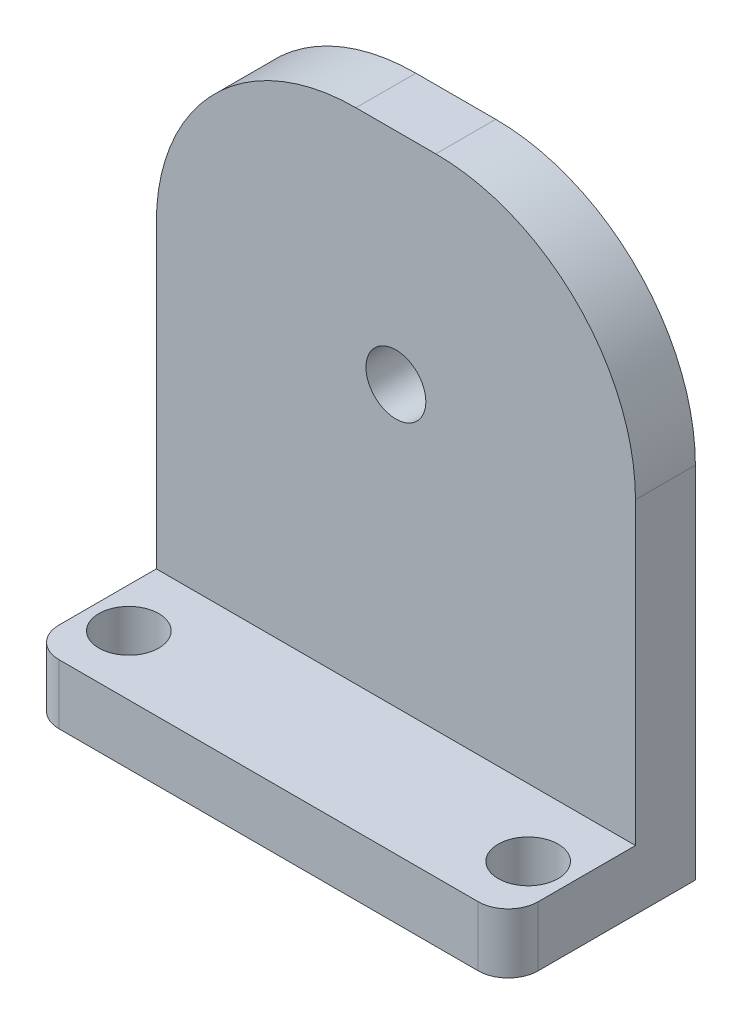
SolidWorks part; units mm, degrees
ref_plane "Front Plane" through (0, 0, 0) normal (0, 0, 1) x (1, 0, 0)
ref_plane "Top Plane" through (0, 0, 0) normal (0, 1, 0) x (1, 0, 0)
ref_plane "Right Plane" through (0, 0, 0) normal (1, 0, 0) x (0, 0, -1)
sketch "Sketch1" plane through (0, 0, 0) normal (0, 1, 0) x (1, 0, 0)
  line L0 (10, 0) -> (-10, 0) construction
  line L1 (12, 3) -> (-12, 3)
  line L2 (12, 3) -> (12, -1.5)
  line L3 (10.5, -3) -> (-10.5, -3)
  line L4 (-12, 3) -> (-12, -1.5)
  line L5 (12, 3) -> (-12, -3) construction
  line L6 (12, -3) -> (-12, 3) construction
  line L7 (-12, 3) -> (-12, 6.3757)
  line L8 (-12, 6.3757) -> (12, 6.3757)
  line L9 (12, 6.3757) -> (12, 3)
  line L10 (-12, 3) -> (11.5558, 3)
  circle A0 centre (-10, 0) radius 1.5
  circle A1 centre (10, 0) radius 1.5
  arc A2 (12, -1.5) -> (10.5, -3) centre (10.5, -1.5) cw
  arc A3 (-10.5, -3) -> (-12, -1.5) centre (-10.5, -1.5) cw
  point P0 (0, 0)
  point P9 (0, 0)
  dimension "D4" = 3
  dimension "D5" = 3
  dimension "D6" = 1.5
  dimension "D1" = 20
  dimension "D2" = 24
  dimension "D3" = 6
extrude "Boss-Extrude1" add sketch "Sketch1" along normal blind 3 contours L9 L8 L7 L1 | A3 L3 A2 L2 L1 L4 A1 A0
sketch "Sketch2" plane through (0, 3, 0) normal (0, 1, 0) x (1, 0, 0)
  line L0 (-12, 6.3757) -> (-12, 3.3757)
  line L1 (-12, -1.5) -> (-12, 6.3757) construction
  line L2 (-12, 3.3757) -> (12, 3.3757)
  line L3 (12, 6.3757) -> (12, -1.5) construction
  line L4 (12, 3.3757) -> (12, 6.3757)
  line L5 (-12, 6.3757) -> (12, 6.3757) construction
  line L6 (12, 6.3757) -> (-12, 6.3757)
  dimension "D1" = 3
extrude "Boss-Extrude2" add sketch "Sketch2" along normal blind 25 contours L6 L0 L2 L4
fillet "Fillet1" radius 10 2 edges at (-12, 28, -4.8757) (12, 28, -4.8757)
sketch "Sketch3" plane through (0, 0, -3.3757) normal (0, 0, 1) x (1, 0, 0)
  line L0 (0, -6.6141) -> (0, 31.9715) construction
  line L1 (-12, 3) -> (12, 3) construction
  circle A0 centre (0, 17) radius 1.5
  dimension "D1" = 3
  dimension "D2" = 14
extrude "Cut-Extrude1" cut sketch "Sketch3" against normal through all
